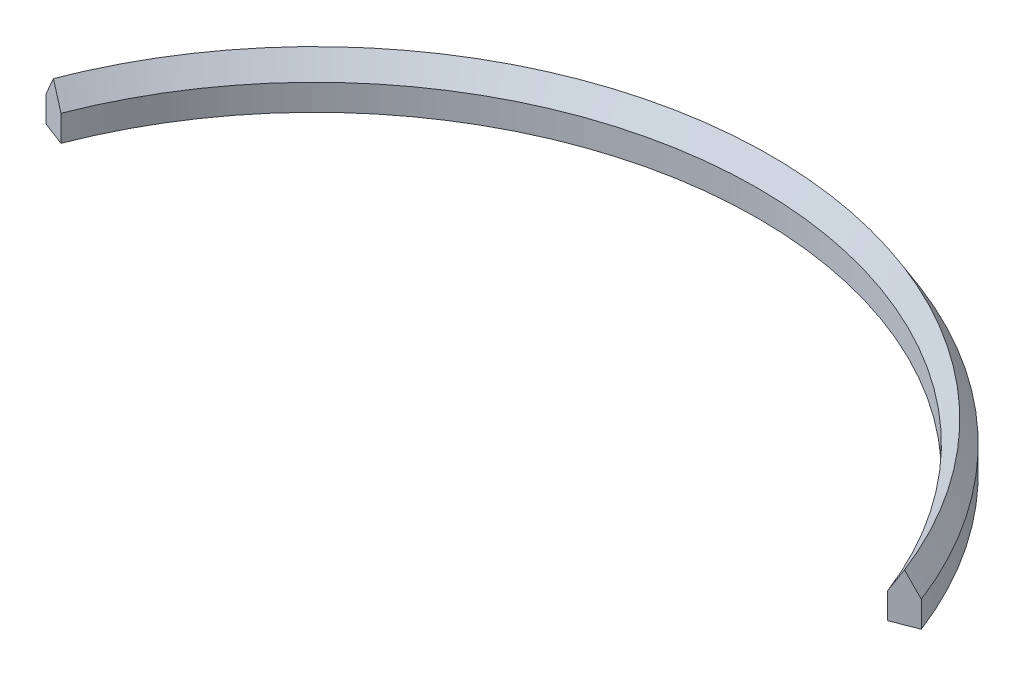
SolidWorks part; units mm, degrees
ref_plane "Front Plane" through (0, 0, 0) normal (0, 0, 1) x (1, 0, 0)
ref_plane "Top Plane" through (0, 0, 0) normal (0, 1, 0) x (1, 0, 0)
ref_plane "Right Plane" through (0, 0, 0) normal (1, 0, 0) x (0, 0, -1)
sketch "PropShadow" plane through (0, 0, 0) normal (0, 1, 0) x (1, 0, 0)
  line L0 (-39.25, 15.1382) -> (39.25, 15.1382) construction
  line L1 (39.25, 15.1382) -> (5.4459, 41.7142) construction
  line L2 (5.4459, 41.7142) -> (-39.25, 15.1382) construction
  line L3 (0, 0) -> (5.4459, 41.7142) construction
  line L4 (0, 0) -> (39.25, 15.1382) construction
  line L5 (-39.25, 15.1382) -> (0, 0) construction
  arc A0 (39.25, 15.1382) -> (-39.25, 15.1382) centre (0, 0) ccw
  point P3 (-39.25, 15.1382)
  point P4 (39.25, 15.1382)
  point P5 (5.4459, 41.7142)
  dimension "D1" = 78.5
  dimension "D2" = 52
  dimension "D3" = 43
  dimension "prop_radius" = 42.0681
  dimension "D5" = 137.818
ref_plane "PropEndPlane" through (0, 0, 0) normal (-0.3599, 0, 0.933) x (0.933, 0, 0.3599)
sketch "Sketch4" plane through (0, 0, 0) normal (-0.3599, 0, 0.933) x (0.933, 0, 0.3599)
  line L0 (-43.2681, 1.2) -> (-42.0681, 3.2)
  line L1 (-40.8681, 1.2) -> (-43.2681, 1.2) construction
  line L2 (-40.8681, 1.2) -> (-40.8681, -1.2)
  line L3 (-40.8681, -1.2) -> (-43.2681, -1.2)
  line L4 (-43.2681, 1.2) -> (-43.2681, -1.2)
  line L5 (-40.8681, 1.2) -> (-43.2681, -1.2) construction
  line L6 (-40.8681, -1.2) -> (-43.2681, 1.2) construction
  line L7 (-42.0681, 3.2) -> (-40.8681, 1.2)
  line L8 (-42.0681, 3.2) -> (-42.0681, 1.2) construction
  point P0 (-42.0681, 0)
  dimension "D1" = 2.4
  dimension "D2" = 2.4
  dimension "D3" = 4.4
sweep "Sweep1" add profiles "Sketch4" path "PropShadow"
equation "\"prop_height\"= 4.4mm"
equation "\"prop_th\"= 2.4mm"
equation "\"prop_indent_height\"= 2.4mm"
equation "\"D1@Sketch4\"=\"prop_th\""
equation "\"D2@Sketch4\"=\"prop_indent_height\""
equation "\"D3@Sketch4\"=\"prop_height\""
